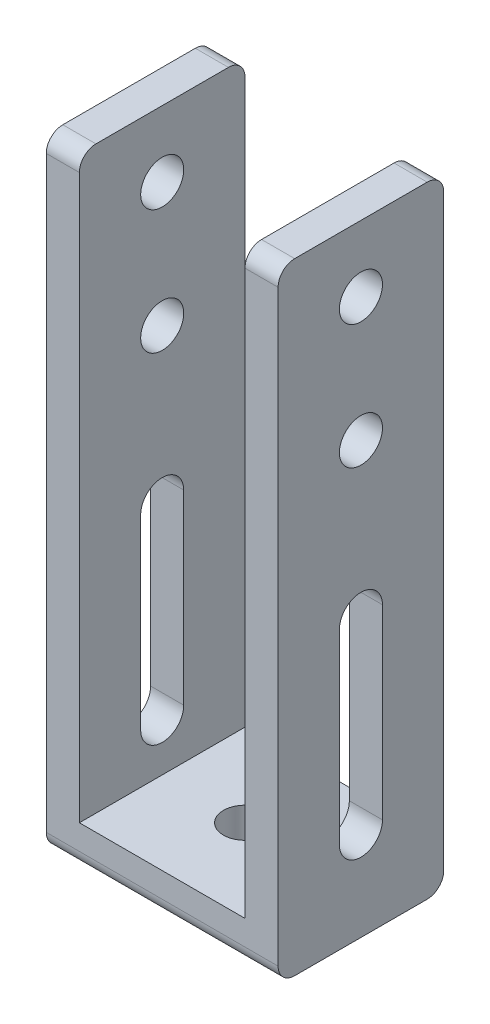
SolidWorks part; units mm, degrees
ref_plane "Front Plane" through (0, 0, 0) normal (0, 0, 1) x (1, 0, 0)
ref_plane "Top Plane" through (0, 0, 0) normal (0, 1, 0) x (1, 0, 0)
ref_plane "Right Plane" through (0, 0, 0) normal (1, 0, 0) x (0, 0, -1)
sketch "Sketch1" plane through (0, 0, 0) normal (0, 1, 0) x (1, 0, 0)
  line L1 (-14, 10) -> (14, 10)
  line L2 (-14, 10) -> (-14, -10)
  line L3 (-14, -10) -> (14, -10)
  line L4 (14, 10) -> (14, -10)
  line L5 (-14, 10) -> (14, -10) construction
  line L6 (-14, -10) -> (14, 10) construction
  point P0 (0, 0)
  dimension "D1" = 28
  dimension "D2" = 20
extrude "Boss-Extrude1" add sketch "Sketch1" along normal blind 5
sketch "Sketch2" plane through (0, 5, 0) normal (0, 1, 0) x (1, 0, 0)
  line L0 (-14, -10) -> (14, -10) construction
  line L1 (-14, 10) -> (-10, 10)
  line L2 (-14, 10) -> (-14, -10)
  line L3 (-14, -10) -> (-10, -10)
  line L4 (-10, 10) -> (-10, -10)
  line L6 (14, 10) -> (10, 10)
  line L7 (14, 10) -> (14, -10)
  line L8 (14, -10) -> (10, -10)
  line L9 (10, 10) -> (10, -10)
  dimension "D1" = 4
  dimension "D2" = 4
extrude "Boss-Extrude2" add sketch "Sketch2" along normal blind 70
sketch "Sketch3" plane through (0, 0, 0) normal (0, -1, 0) x (1, 0, 0)
  circle A0 centre (0, 0) radius 2.6
  dimension "D1" = 5.2
extrude "Cut-Extrude1" cut sketch "Sketch3" against normal blind 5
sketch "Sketch4" plane through (14, 0, 0) normal (1, 0, 0) x (0, 0, -1)
  line L0 (0, 75) -> (0, 67) construction
  line L1 (-10, 75) -> (10, 75) construction
  line L2 (0, 67) -> (0, 52) construction
  line L3 (0, 52) -> (0, 33.5) construction
  line L4 (0, 33.5) -> (0, 11) construction
  line L5 (2.6, 33.5) -> (2.6, 11)
  line L6 (-2.6, 33.5) -> (-2.6, 11)
  circle A0 centre (0, 67) radius 2.6
  circle A1 centre (0, 52) radius 2.6
  arc A2 (2.6, 33.5) -> (-2.6, 33.5) centre (0, 33.5) ccw
  arc A3 (-2.6, 11) -> (2.6, 11) centre (0, 11) ccw
  dimension "D5" = 5.2
  dimension "D1" = 8
  dimension "D2" = 15
  dimension "D3" = 18.5
  dimension "D4" = 22.5
extrude "Cut-Extrude2" cut sketch "Sketch4" against normal blind 40
fillet "Fillet1" radius 2 6 edges at (0, 0, 10) (0, 0, -10) (12, 75, -10) (-12, 75, -10) (-12, 75, 10) (12, 75, 10)
